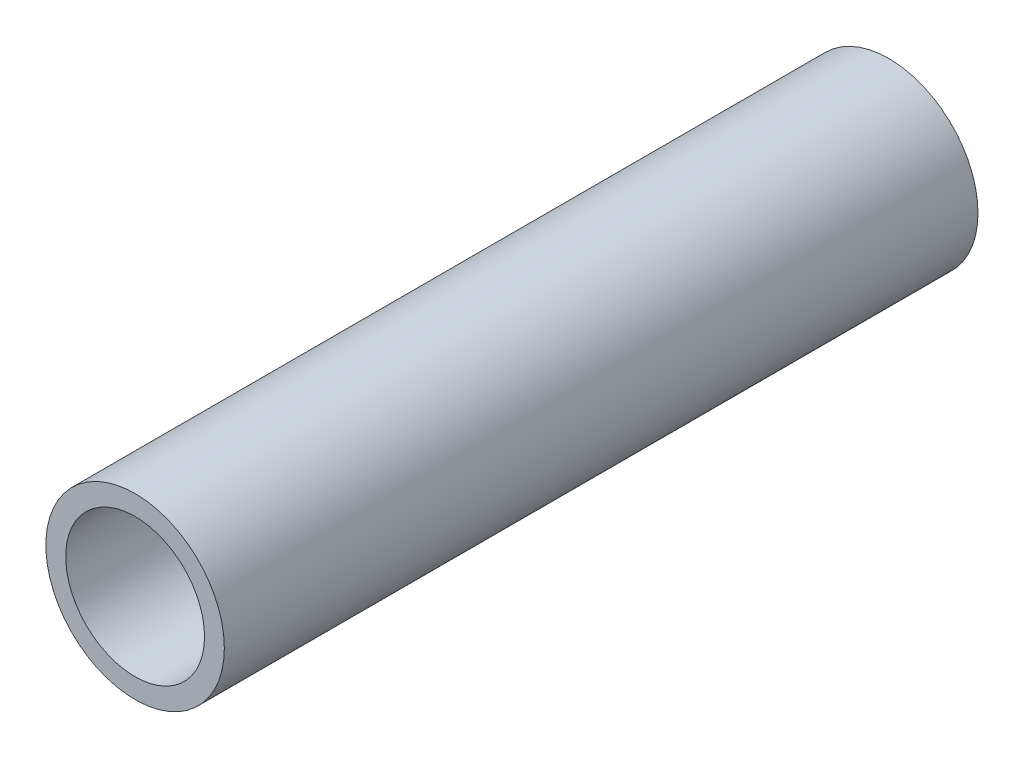
SolidWorks part; units mm, degrees
ref_plane "前视基准面" through (0, 0, 0) normal (0, 0, 1) x (1, 0, 0)
ref_plane "上视基准面" through (0, 0, 0) normal (0, 1, 0) x (1, 0, 0)
ref_plane "右视基准面" through (0, 0, 0) normal (1, 0, 0) x (0, 0, -1)
sketch "草图1" plane through (0, 0, 0) normal (0, 0, 1) x (1, 0, 0)
  circle A0 centre (0, 0) radius 7
  circle A1 centre (0, 0) radius 9
  dimension "D1" = 18
  dimension "D2" = 14
extrude "拉伸1" add sketch "草图1" along normal blind 76
